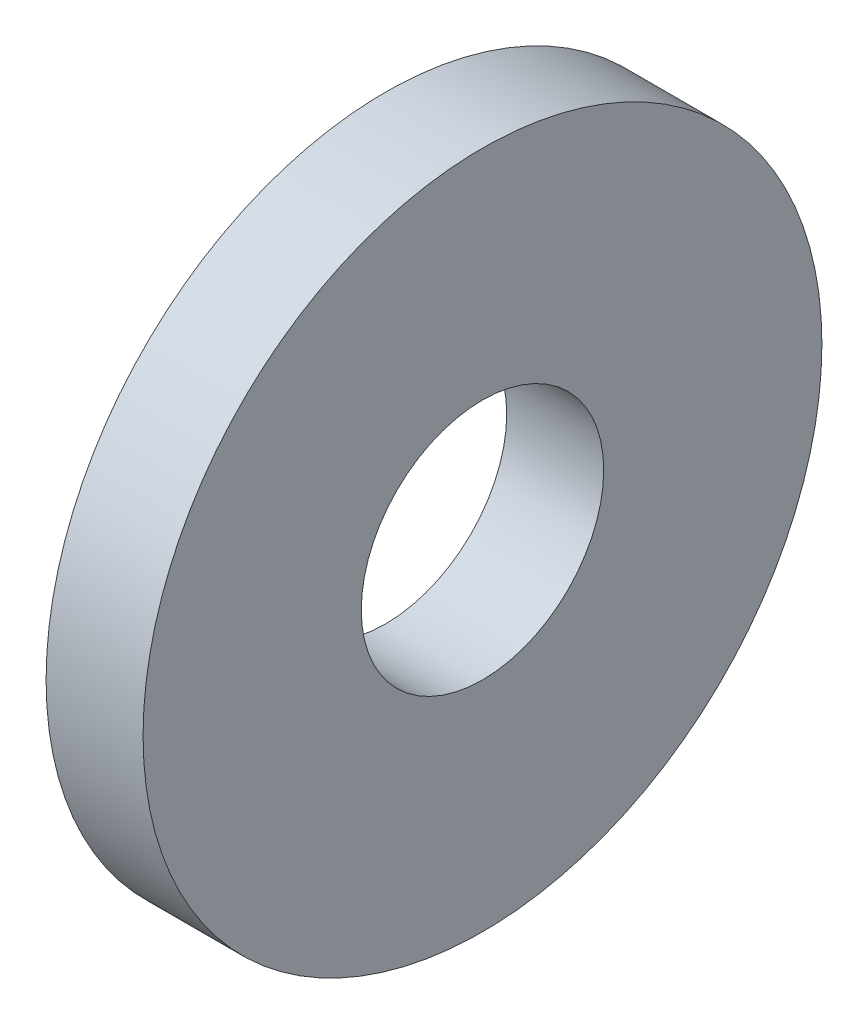
SolidWorks part; units mm, degrees
ref_plane "Plane1" through (0, 0, 0) normal (0, 0, 1) x (1, 0, 0)
ref_plane "Plane2" through (0, 0, 0) normal (0, 1, 0) x (1, 0, 0)
ref_plane "Plane3" through (0, 0, 0) normal (1, 0, 0) x (0, 0, -1)
sketch "Sketch1" plane through (0, 0, 0) normal (1, 0, 0) x (0, 0, -1)
  circle A0 centre (0, 0) radius 1.25
  circle A1 centre (0, 0) radius 3.5
  dimension "Insid_dia" = 2.5
  dimension "OutsideDia" = 7
extrude "Base-Extrude" add sketch "Sketch1" along normal blind 1
